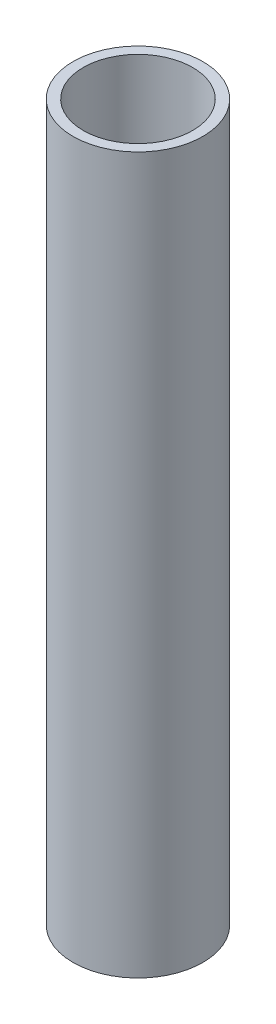
SolidWorks part; units mm, degrees
ref_plane "Front Plane" through (0, 0, 0) normal (0, 0, 1) x (1, 0, 0)
ref_plane "Top Plane" through (0, 0, 0) normal (0, 1, 0) x (1, 0, 0)
ref_plane "Right Plane" through (0, 0, 0) normal (1, 0, 0) x (0, 0, -1)
sketch "Sketch1" plane through (0, 0, 0) normal (0, 1, 0) x (1, 0, 0)
  circle A0 centre (0, 0) radius 6.35
  circle A1 centre (0, 0) radius 5.35
extrude "Boss-Extrude1" add sketch "Sketch1" along normal blind 70
